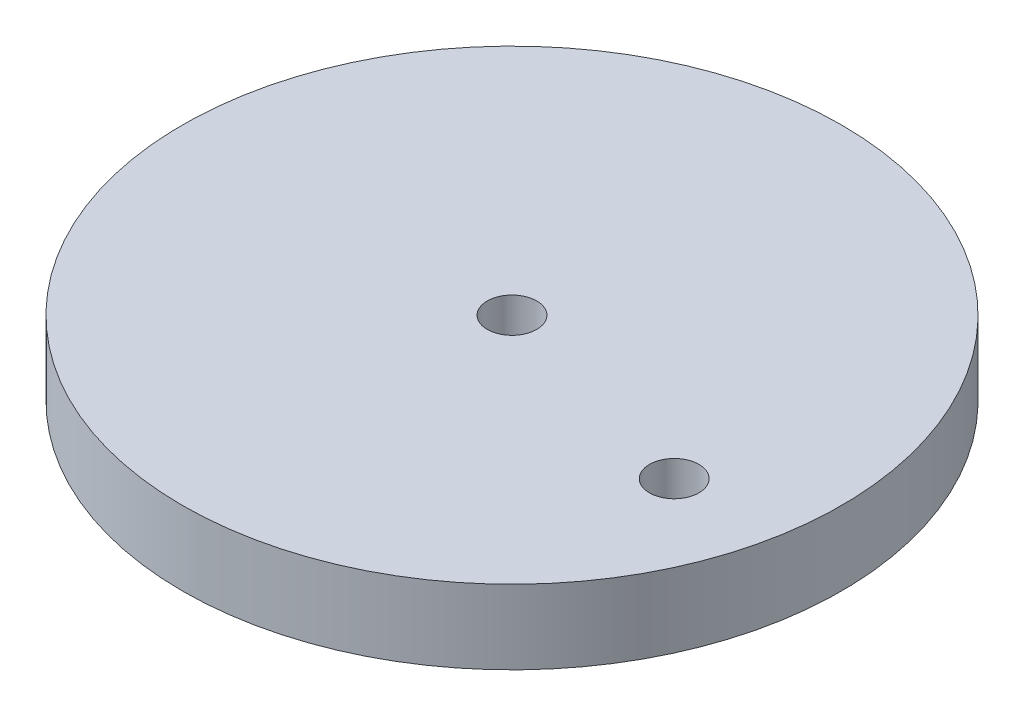
SolidWorks part; units mm, degrees
ref_plane "Front Plane" through (0, 0, 0) normal (0, 0, 1) x (1, 0, 0)
ref_plane "Top Plane" through (0, 0, 0) normal (0, 1, 0) x (1, 0, 0)
ref_plane "Right Plane" through (0, 0, 0) normal (1, 0, 0) x (0, 0, -1)
sketch "Sketch1" plane through (0, 0, 0) normal (0, 1, 0) x (1, 0, 0)
  circle A0 centre (0, 0) radius 20
  circle A1 centre (0, 0) radius 1.5
  circle A2 centre (13.5109, -3.6681) radius 1.5
  dimension "D1" = 40
  dimension "D2" = 3
extrude "Boss-Extrude1" add sketch "Sketch1" along normal mid plane 4.5
